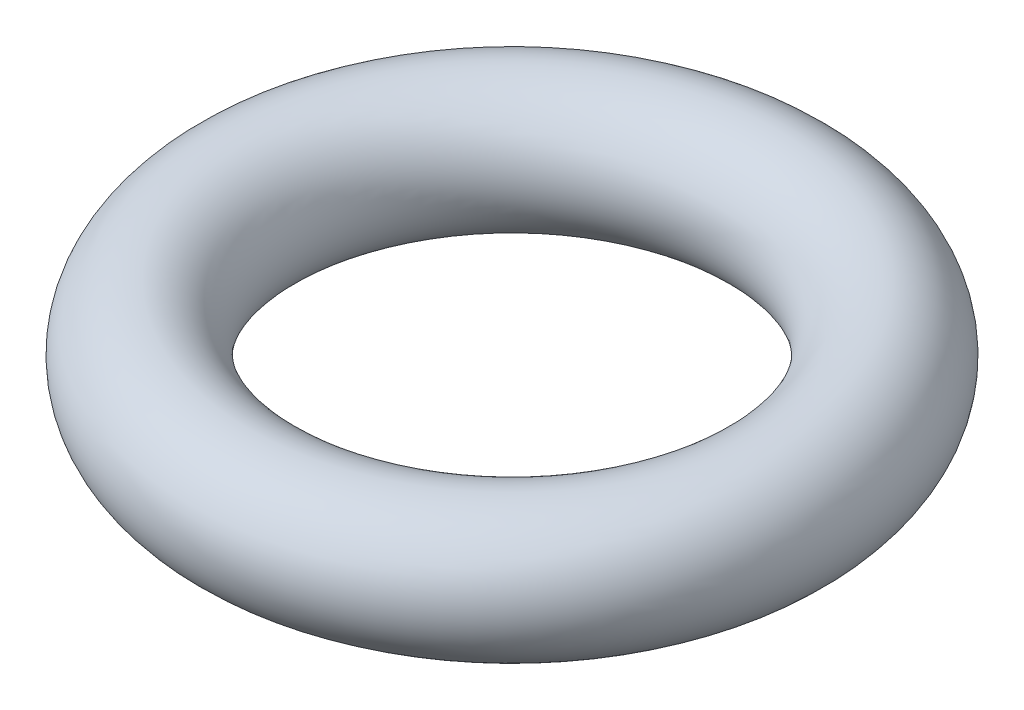
SolidWorks part; units mm, degrees
material "BUTYL"
ref_plane "Front Plane" through (0, 0, 0) normal (0, 0, 1) x (1, 0, 0)
ref_plane "Top Plane" through (0, 0, 0) normal (0, 1, 0) x (1, 0, 0)
ref_plane "Right Plane" through (0, 0, 0) normal (1, 0, 0) x (0, 0, -1)
sketch "Sketch1" plane through (0, 0, 0) normal (0, 0, 1) x (1, 0, 0)
  line L0 (0, 0) -> (0, 1.1966) construction
  circle A0 centre (-3, 0) radius 0.75
  dimension "D1" = 1.5
  dimension "D2" = 3
revolve "Revolve1" add sketch "Sketch1" angle 360 about L0
